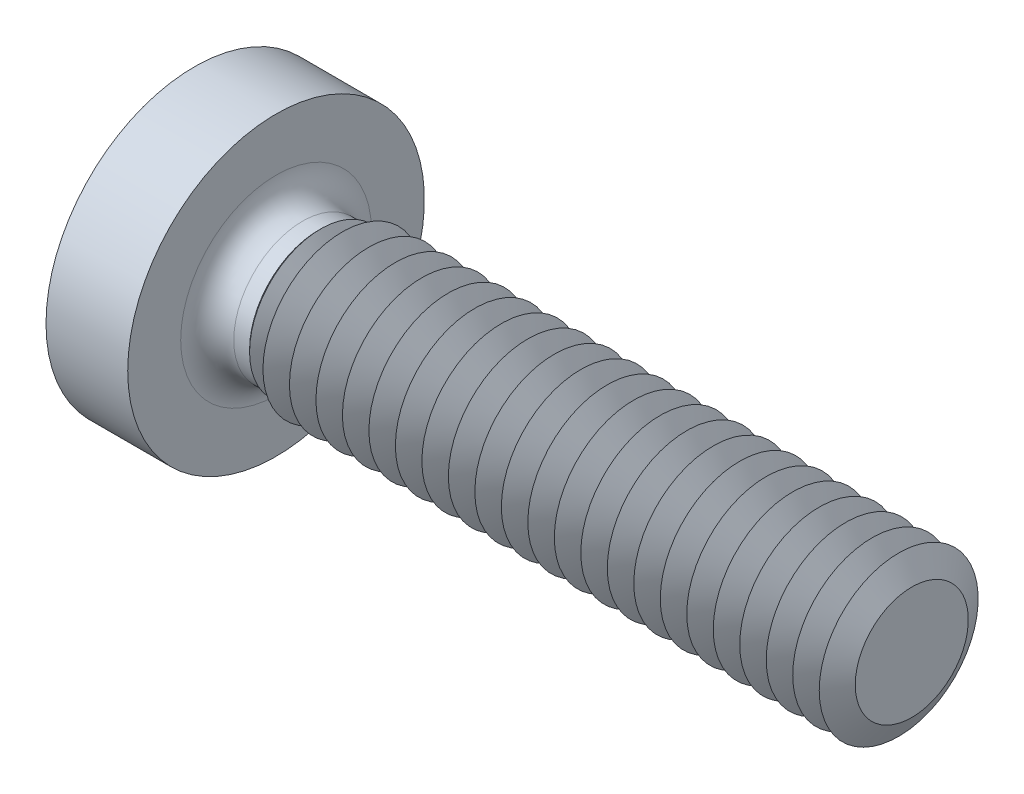
SolidWorks part; units mm, degrees
revolve "基体-旋转" add sketch "草图2" angle 360 about L0
sketch "草图2" plane through (0, 0, 0) normal (0, 0, 1) x (1, 0, 0)
  line L0 (-1.3318, 0) -> (6.5885, 0) construction
  line L1 (0, 0) -> (14.4, 0)
  line L2 (14.4, 0) -> (14.4, 1.5)
  line L3 (14.4, 1.5) -> (3.4, 1.5)
  line L4 (3.4, 1.5) -> (3.199, 1.299)
  line L5 (3.199, 1.299) -> (2.901, 1.299)
  line L6 (2.4, 1.8) -> (2.4, 2.8)
  line L7 (2.4, 2.8) -> (0.8575, 2.8)
  arc A0 (2.4, 1.8) -> (2.901, 1.299) centre (2.901, 1.8) ccw
  arc A1 (0, 0) -> (0.8575, 2.8) centre (5, 0) cw
  dimension "D3" = 5
  dimension "dk" = 5.6
  dimension "d" = 3
  dimension "l" = 12
  dimension "a" = 1
  dimension "D1" = 45
  dimension "D2" = 2.598
  dimension "da" = 3.6
  dimension "k" = 2.4
cosmetic thread "装饰螺纹线1" parameters "D1"=11, "D2"=2.598
ref_plane "前视" through (0, 0, 0) normal (0, 0, 1) x (1, 0, 0)
ref_plane "上视" through (0, 0, 0) normal (0, 1, 0) x (1, 0, 0)
ref_plane "右视" through (0, 0, 0) normal (1, 0, 0) x (0, 0, -1)
sketch "尺寸草图" plane through (0, 0, 0) normal (0, 0, 1) x (1, 0, 0)
  line L0 (0, 0) -> (12, 0)
  line L1 (0, 0) -> (0, 5.6)
  line L2 (12, 0) -> (12, 3.6)
  point P5 (0, 3)
  point P6 (11.5, 0)
  point P7 (1, 0)
  point P8 (2.4, 0)
  point P9 (7, 0)
  point P10 (3, 0)
  point P11 (10.2, 0)
  dimension "dk" = 5.6
  dimension "d" = 3
  dimension "l" = 12
  dimension "a" = 1
  dimension "da" = 3.6
  dimension "k" = 2.4
  dimension "P" = 0.5
  dimension "rf" = 5
  dimension "m" = 3
  dimension "h" = 1.8
sketch "草图3" plane through (0, 0, 0) normal (0, 0, 1) x (1, 0, 0)
  line L0 (14.1527, 1.5) -> (14.6527, 1.5)
  line L1 (14.6527, 1.5) -> (14.4, 1.067)
  line L2 (14.4, 1.067) -> (14.1527, 1.5)
  line L3 (14.4, 1.5) -> (3.4, 1.5) construction
  line L4 (14.4, -1.5) -> (14.4, 1.5) construction
  line L5 (-0.2428, 0) -> (7.1644, 0) construction
  line L6 (-1.3318, 0) -> (6.5885, 0) construction
  dimension "P" = 0.5
  dimension "D1" = 0.433
  dimension "D2" = 60
revolve "切除-旋转1" cut sketch "草图3" angle 360 about L5
sketch "草图5" plane through (0, 0, 0) normal (1, 0, 0) x (0, 0, -1)
  line L1 (0.25, 1.5) -> (-0.25, 1.5)
  line L2 (0.25, 1.5) -> (0.25, -1.5)
  line L3 (0.25, -1.5) -> (-0.25, -1.5)
  line L4 (-0.25, 1.5) -> (-0.25, -1.5)
  point P4 (0.25, 0)
  point P5 (0, 1.5)
  dimension "m" = 3
  dimension "D1" = 0.5
ref_plane "基准面1" through (1.8, 0, 0) normal (1, 0, 0) x (0, 0, -1)
pattern_linear "阵列(线性)1" count 23 spacing 0.5 along (-1, 0, 0) of "切除-旋转1"
sketch "草图6" plane through (1.8, 0, 0) normal (1, 0, 0) x (0, 0, -1)
  point P0 (0, 0)
loft "切除-放样1" cut profiles "草图6", "草图5"
ref_plane "基准面2" through (0, 0, 0) normal (0, -0.7071, 0.7071) x (1, 0, 0)
mirror "镜向1" about plane through (0, 0, 0) normal (0, -0.7071, 0.7071) of "切除-放样1"
equation "\"l@草图2\" = \"l@尺寸草图\""
equation "\"dk@草图2\" = \"dk@尺寸草图\""
equation "\"k@草图2\" = \"k@尺寸草图\""
equation "\"D2@草图2\" = \"d@尺寸草图\"*0.866"
equation "\"a@草图2\" = \"a@尺寸草图\""
equation "\"D3@草图2\" = \"rf@尺寸草图\""
equation "\"d@草图2\" = \"d@尺寸草图\""
equation "\"da@草图2\" = \"da@尺寸草图\""
equation "\"D2@装饰螺纹线1\" = \"d@尺寸草图\"*0.866"
equation "\"D1@装饰螺纹线1\" = \"l@尺寸草图\"-\"a@尺寸草图\""
equation "\"P@草图3\" = \"P@尺寸草图\""
equation "\"D1@草图3\" = \"P@尺寸草图\"*0.866"
equation "\"h@基准面1\" = \"h@尺寸草图\""
equation "\"D1@草图5\" = \"P@尺寸草图\""
equation "\"m@草图5\" = \"m@尺寸草图\""
equation "\"D3@阵列(线性)1\" = \"P@尺寸草图\""
equation "\"D1@阵列(线性)1\" = (\"l@尺寸草图\"-\"a@尺寸草图\")/\"P@尺寸草图\"+1"
